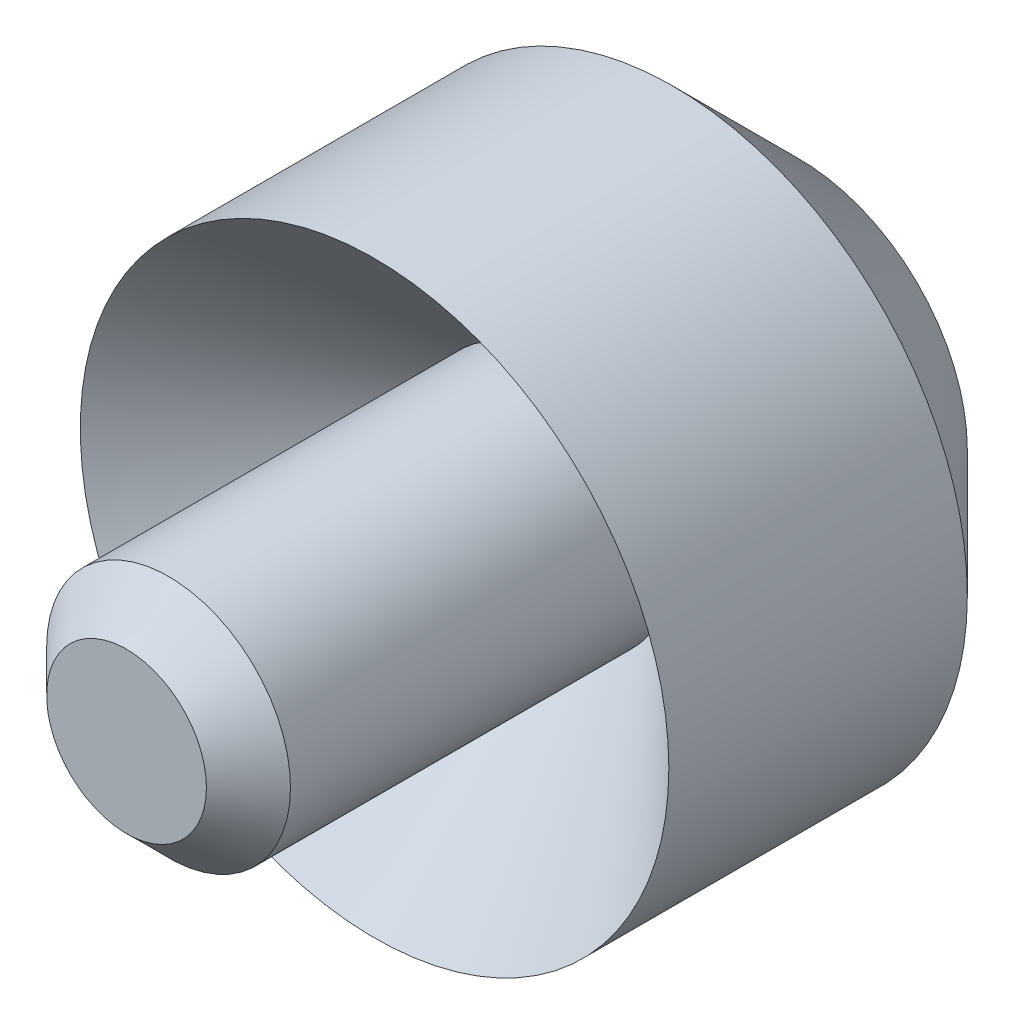
SolidWorks part; units mm, degrees
ref_plane "정면" through (0, 0, 0) normal (0, 0, 1) x (1, 0, 0)
ref_plane "윗면" through (0, 0, 0) normal (0, 1, 0) x (1, 0, 0)
ref_plane "우측면" through (0, 0, 0) normal (1, 0, 0) x (0, 0, -1)
sketch "스케치1" plane through (0, 0, 0) normal (0, 0, 1) x (1, 0, 0)
  circle A0 centre (0, 0) radius 1.45
  dimension "D1" = 2.9
extrude "보스-돌출1" add sketch "스케치1" along normal blind 5
sketch "스케치3" plane through (0, 0, 0) normal (1, 0, 0) x (0, 0, -1)
  line L0 (0, 0) -> (3, 0)
  line L1 (3, 0) -> (3, -2)
  line L2 (3, -2) -> (1.5, -3.5)
  line L3 (1.5, -3.5) -> (-2.05, -3.5)
  line L4 (-2.05, -3.5) -> (0, -1.45)
  line L5 (0, -1.45) -> (0, 0)
  dimension "D1" = 45
  dimension "D2" = 3.5
  dimension "D3" = 3
  dimension "D4" = 135
  dimension "D5" = 2
revolve "회전1" add sketch "스케치3" angle 360 about L0
chamfer "모따기1" distance 0.5 angle 45 1 edges at (1.45, 0, 5)
